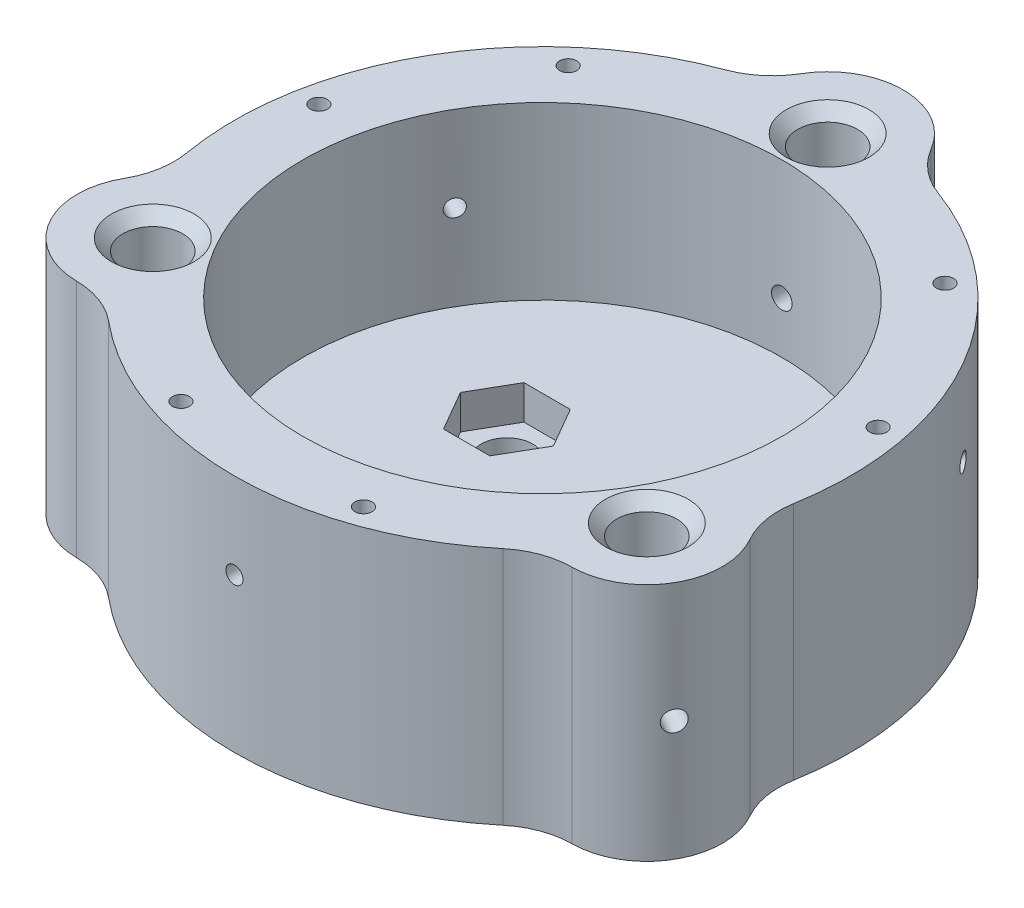
SolidWorks part; units mm, degrees
ref_plane "Спереди" through (0, 0, 0) normal (0, 0, 1) x (1, 0, 0)
ref_plane "Сверху" through (0, 0, 0) normal (0, 1, 0) x (1, 0, 0)
ref_plane "Справа" through (0, 0, 0) normal (1, 0, 0) x (0, 0, -1)
sketch "Эскиз1" plane through (0, 0, 0) normal (0, 1, 0) x (1, 0, 0)
  circle A0 centre (0, 0) radius 25 construction
  circle A1 centre (0, 25) radius 2.625
  circle A3 centre (0, 25) radius 6.625
  circle A4 centre (0, 0) radius 21
  circle A5 centre (0, 0) radius 27
  circle A6 centre (21.6506, -12.5) radius 6.625
  circle A7 centre (21.6506, -12.5) radius 2.625
  circle A8 centre (-21.6506, -12.5) radius 6.625
  circle A9 centre (-21.6506, -12.5) radius 2.625
  dimension "D1" = 50
  dimension "D2" = 5.25
  dimension "D3" = 4
  dimension "D5" = 4
  dimension "D4" = 2
  dimension "D6" = 3
extrude "Бобышка-Вытянуть1" add sketch "Эскиз1" along normal blind 15 contours A5 A3 A1 | A3 A5 A1 A4 | A6 A5 A3 A4 | A8 A4 A3 A5 | A7 A5 A6 A4 | A7 A5 A6 | A8 A5 A6 A4 | A9 A5 A8 | A9 A5 A8 A4
sketch "Эскиз2" plane through (0, 0, 0) normal (0, -1, 0) x (1, 0, 0)
  arc A27 (25.9493, 7.4589) -> (19.4343, 18.7433) centre (21.6506, 12.5) ccw
  arc A28 (6.515, -26.2022) -> (25.9493, 7.4589) centre (0, 0) ccw
  arc A29 (-6.515, -26.2022) -> (6.515, -26.2022) centre (0, -25) ccw
  arc A30 (-25.9493, 7.4589) -> (-6.515, -26.2022) centre (0, 0) ccw
  arc A31 (-19.4343, 18.7433) -> (-25.9493, 7.4589) centre (-21.6506, 12.5) ccw
  arc A32 (19.4343, 18.7433) -> (-19.4343, 18.7433) centre (0, 0) ccw
  arc A33 (25.9493, 7.4589) -> (19.4343, 18.7433) centre (21.6506, 12.5) ccw
  arc A34 (6.515, -26.2022) -> (25.9493, 7.4589) centre (0, 0) ccw
  arc A35 (-6.515, -26.2022) -> (6.515, -26.2022) centre (0, -25) ccw
  arc A36 (-25.9493, 7.4589) -> (-6.515, -26.2022) centre (0, 0) ccw
  arc A37 (-19.4343, 18.7433) -> (-25.9493, 7.4589) centre (-21.6506, 12.5) ccw
  arc A38 (19.4343, 18.7433) -> (-19.4343, 18.7433) centre (0, 0) ccw
  dimension "D1" = 0
extrude "Бобышка-Вытянуть2" add sketch "Эскиз2" along normal blind 6
fillet "Скругление1" radius 7 6 edges at (6.515, 4.5, -26.2022) (-6.515, 4.5, -26.2022) (-25.9493, 4.5, 7.4589) (-19.4343, 4.5, 18.7433) (19.4343, 4.5, 18.7433) (25.9493, 4.5, 7.4589)
chamfer "Фаска1" distance 1 angle 45 3 edges at (0, 15, -22.375) (21.6506, 15, 15.125) (-21.6506, 15, 15.125)
sketch "Эскиз4" plane through (0, -6, 0) normal (0, -1, 0) x (1, 0, 0)
  circle A0 centre (0, 0) radius 8.5 construction
  circle A1 centre (0, 8.5) radius 2.25
  circle A2 centre (7.3612, -4.25) radius 2.25
  circle A3 centre (-7.3612, -4.25) radius 2.25
  dimension "D1" = 17
  dimension "D2" = 4.5
  dimension "D3" = 3
extrude "Вырез-Вытянуть1" cut sketch "Эскиз4" against normal through all
sketch "Эскиз5" plane through (0, 0, 0) normal (0, 1, 0) x (1, 0, 0)
  line L0 (2.0352, -12.025) -> (4.0703, -8.5)
  line L1 (5.3261, 0.725) -> (9.3964, 0.725)
  line L2 (9.3964, 0.725) -> (11.4315, 4.25)
  line L3 (11.4315, 4.25) -> (9.3964, 7.775)
  line L4 (9.3964, 7.775) -> (5.3261, 7.775)
  line L5 (5.3261, 7.775) -> (3.2909, 4.25)
  line L6 (3.2909, 4.25) -> (5.3261, 0.725)
  line L7 (4.0703, -8.5) -> (2.0352, -4.975)
  line L8 (2.0352, -4.975) -> (-2.0352, -4.975)
  line L9 (-2.0352, -4.975) -> (-4.0703, -8.5)
  line L10 (-4.0703, -8.5) -> (-2.0352, -12.025)
  line L11 (-2.0352, -12.025) -> (2.0352, -12.025)
  line L12 (-11.4315, 4.25) -> (-9.3964, 0.725)
  line L13 (-9.3964, 0.725) -> (-5.3261, 0.725)
  line L14 (-5.3261, 0.725) -> (-3.2909, 4.25)
  line L15 (-3.2909, 4.25) -> (-5.3261, 7.775)
  line L16 (-5.3261, 7.775) -> (-9.3964, 7.775)
  line L17 (-9.3964, 7.775) -> (-11.4315, 4.25)
  circle A2 centre (7.3612, 4.25) radius 3.525 construction
  circle A3 centre (0, -8.5) radius 3.525 construction
  circle A4 centre (-7.3612, 4.25) radius 3.525 construction
  circle A5 centre (0, -8.5) radius 2.25 construction
  dimension "D1" = 7.05
  dimension "D2" = 3
extrude "Вырез-Вытянуть2" cut sketch "Эскиз5" against normal blind 3
sketch "Эскиз6" plane through (0, 15, 0) normal (0, 1, 0) x (1, 0, 0)
  line L0 (0, 0) -> (0, -25) construction
  line L1 (-8, -23.6854) -> (8, -23.6854) construction
  circle A0 centre (0, 0) radius 25 construction
  circle A1 centre (-8, -23.6854) radius 0.75
  circle A2 centre (8, -23.6854) radius 0.75
  circle A3 centre (-16.5122, 18.7709) radius 0.75
  circle A4 centre (-24.5122, 4.9145) radius 0.75
  circle A5 centre (24.5122, 4.9145) radius 0.75
  circle A6 centre (16.5122, 18.7709) radius 0.75
  dimension "D2" = 1.5
  dimension "D3" = 1.5
  dimension "D1" = 16
  dimension "D4" = 3
extrude "Вырез-Вытянуть3" cut sketch "Эскиз6" against normal through all
sketch "Эскиз7" plane through (0, 0, 0) normal (0, 0, 1) x (1, 0, 0)
  line L0 (17.2802, 15) -> (-17.2802, 15) construction
  line L1 (0, 15) -> (0, 0) construction
  circle A0 centre (0, 7.5) radius 0.75
  dimension "D1" = 1.5
extrude "Вырез-Вытянуть4" cut sketch "Эскиз7" along normal through all
pattern_circular "Круговой массив1" count 3 over 360 about axis through (0, 15, 0) along (0, -1, 0) of "Вырез-Вытянуть4"
ref_plane "Плоскость1" through (0, 0, -31.625) normal (0, 0, -1) x (-1, 0, 0)
sketch "Эскиз8" plane through (0, 0, -31.625) normal (0, 0, -1) x (-1, 0, 0)
  line L0 (0, 15) -> (0, -6) construction
  line L1 (5.7106, 15) -> (-5.7106, 15) construction
  line L2 (-5.7106, -6) -> (5.7106, -6) construction
  circle A0 centre (0, 4.5) radius 0.9
  dimension "D1" = 1.8
extrude "Вырез-Вытянуть5" cut sketch "Эскиз8" against normal up to surface (10.6443 mm away)
pattern_circular "Круговой массив2" count 3 over 360 about axis through (0, 15, 0) along (0, -1, 0) of "Вырез-Вытянуть5"
equation "\"motor_diameter\"= 30"
equation "\"mm_diameter\"= IIF ( \"motor_diameter\" < 34 , 41 , \"motor_diameter\" + 8 )"
equation "\"upper_shafts_diameter\"= 5"
equation "\"upper_shats_length\"= 180"
equation "\"upper_bearing_d1\"= 10"
equation "\"upper_bearing_d2\"= 5"
equation "\"upper_bearing_h\"= 15"
equation "\"lower_shafts_diameter\"= 5"
equation "\"lower_shafts_length\"= 180"
equation "\"lower_bearing_d1\"= 10"
equation "\"lower_bearing_d2\"= 5"
equation "\"lower_bearing_h\"= 15"
equation "\"print_offset\"= 0.5"
equation "\"bh_screws_d\"= 2"
equation "\"bh_screws_h\"= 20"
equation "\"bh_screws_hh_d\"= 3.4"
equation "\"bh_screws_hh_h\"= 2"
equation "\"bh_nut_d\"= 3.8"
equation "\"bh_nut_h\"= 2"
equation "\"motor_screws_d\"= 3"
equation "\"motor_screws_h\"= 16"
equation "\"motor_screws_hh_d\"= 5.5"
equation "\"motor_screws_hh_h\"= 3"
equation "\"plate_hole_distance\"= 25.4"
equation "\"plate_screws_d\"= 6.5"
equation "\"shafts_diameter\"= IIF ( \"mm_diameter\" < 42 , 42 + 8 , \"mm_diameter\" + 8 )"
equation "\"central_hole_diameter\"= 8"
equation "\"bh_thikness\"= 4"
equation "\"D1@Эскиз1\"=\"shafts_diameter\""
equation "\"D2@Эскиз1\" = \"upper_shafts_diameter\" + \"print_offset\" / 2"
equation "\"D3@Эскиз1\"=\"bh_thikness\""
equation "\"D1@Бобышка-Вытянуть1\"= \"upper_bearing_h\""
equation "\"D1@Бобышка-Вытянуть2\"=6"
equation "\"D4@Эскиз1\"=\"D3@Эскиз1\"/2"
equation "\"D2@Эскиз4\"=\"ends_screws_d\"+\"print_offset\""
equation "\"D1@Эскиз5\"=\"ends_nut_d\"+\"print_offset\"/2"
equation "\"D1@Вырез-Вытянуть2\"=\"ends_nut_h\""
equation "\"D5@Эскиз1\"=\"bh_thikness\""
equation "\"ends_screws_d\"= 4"
equation "\"ends_screws_h\"= 16"
equation "\"ends_screws_hh_d\"= 6.7"
equation "\"ends_screws_hh_h\"= 4.1"
equation "\"ends_nut_d\"= 6.8"
equation "\"ends_nut_h\"= 3"
equation "\"D2@Эскиз6\"=\"bh_screws_d\"-\"print_offset\""
equation "\"D3@Эскиз6\"=\"D2@Эскиз6\""
equation "\"D1@Эскиз7\"=\"bh_screws_d\"-\"print_offset\""
equation "\"D1@Эскиз8\"=\"bh_screws_d\"-0.2"
